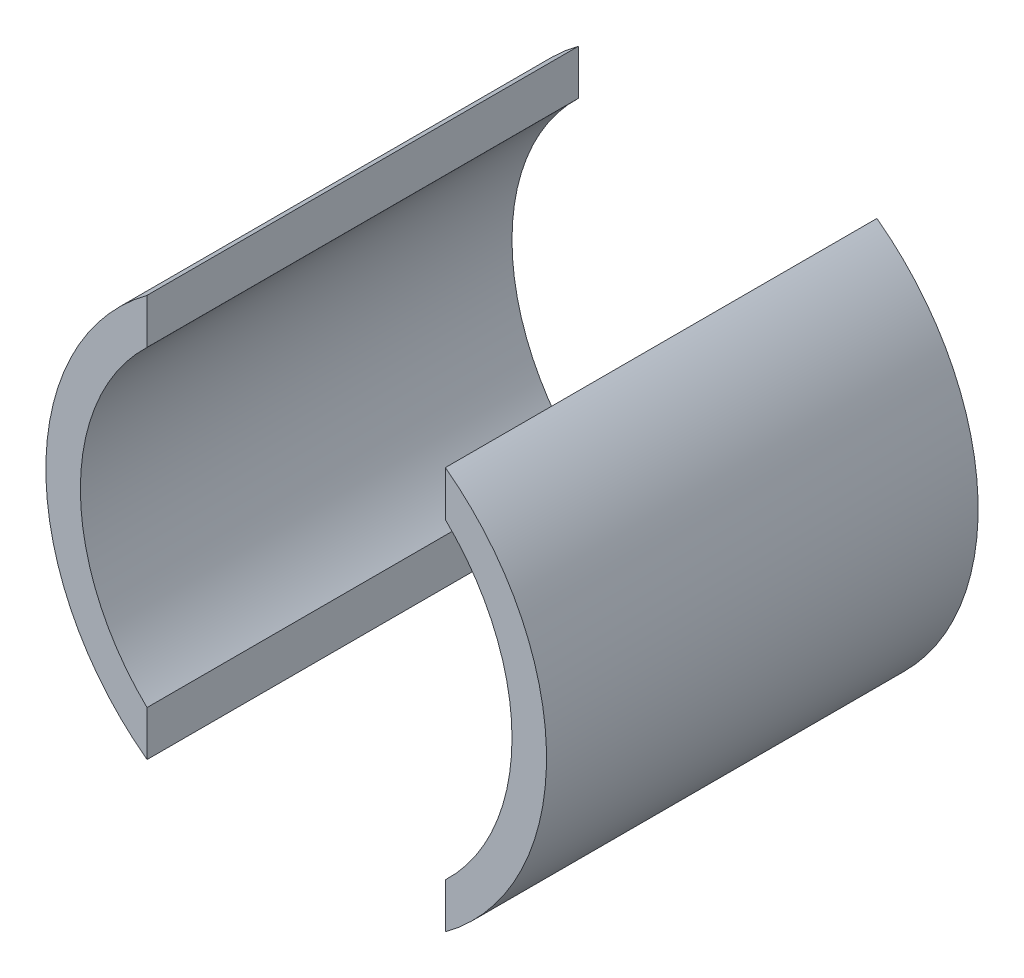
SolidWorks part; units mm, degrees
ref_plane "Front Plane" through (0, 0, 0) normal (0, 0, 1) x (1, 0, 0)
ref_plane "Top Plane" through (0, 0, 0) normal (0, 1, 0) x (1, 0, 0)
ref_plane "Right Plane" through (0, 0, 0) normal (1, 0, 0) x (0, 0, -1)
sketch "Sketch1" plane through (0, 0, 0) normal (0, 0, 1) x (1, 0, 0)
  line L0 (-17.2808, -18.0658) -> (-17.2808, -23.2889)
  line L2 (-17.2808, 23.2889) -> (-17.2808, 18.0658)
  line L4 (17.2808, 23.2889) -> (17.2808, 18.0658)
  line L7 (17.2808, -18.0658) -> (17.2808, -23.2889)
  arc A0 (-17.2808, 23.2889) -> (-17.2808, -23.2889) centre (0, 0) ccw
  arc A1 (-17.2808, 18.0658) -> (-17.2808, -18.0658) centre (0, 0) ccw
  arc A2 (17.2808, -18.0658) -> (17.2808, 18.0658) centre (0, 0) ccw
  arc A3 (17.2808, -23.2889) -> (17.2808, 23.2889) centre (0, 0) ccw
  dimension "D1" = 58
  dimension "D2" = 50
extrude "Boss-Extrude1" add sketch "Sketch1" along normal blind 50
